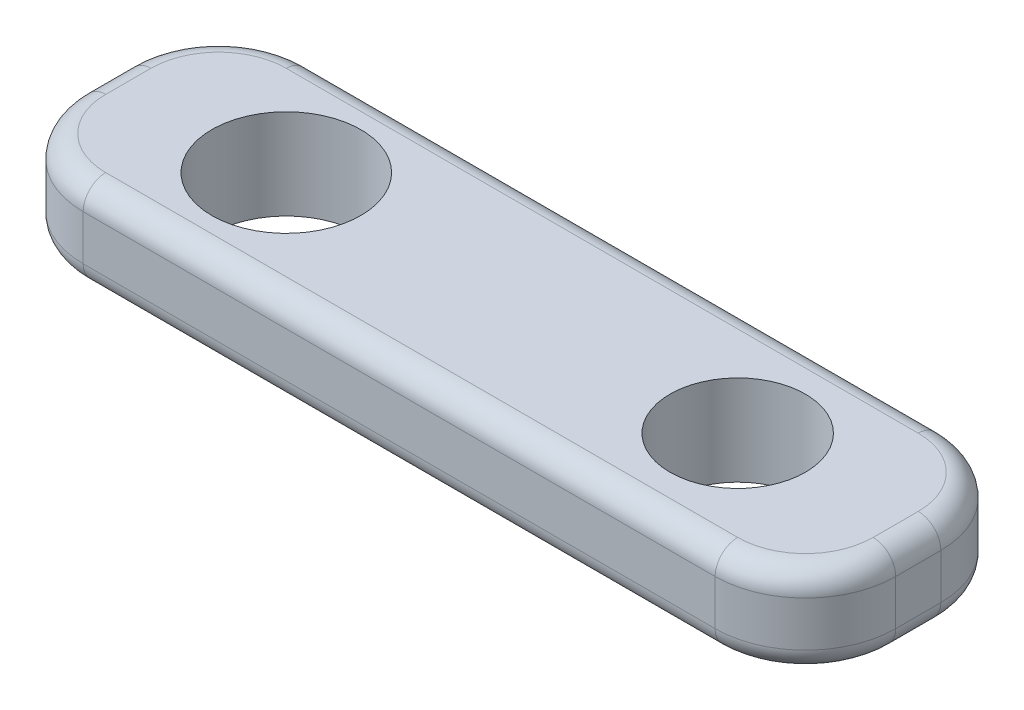
SolidWorks part; units mm, degrees
ref_plane "前视基准面" through (0, 0, 0) normal (0, 0, 1) x (1, 0, 0)
ref_plane "上视基准面" through (0, 0, 0) normal (0, 1, 0) x (1, 0, 0)
ref_plane "右视基准面" through (0, 0, 0) normal (1, 0, 0) x (0, 0, -1)
sketch "草图1" plane through (0, 0, 0) normal (0, 1, 0) x (1, 0, 0)
  line L13 (-7, 2.5) -> (7, 2.5)
  line L14 (-9, 0.5) -> (-9, -0.5)
  line L15 (-7, -2.5) -> (7, -2.5)
  line L16 (9, 0.5) -> (9, -0.5)
  line L17 (-9, 2.5) -> (9, -2.5) construction
  line L18 (-9, -2.5) -> (9, 2.5) construction
  arc A6 (7, 2.5) -> (9, 0.5) centre (7, 0.5) cw
  arc A7 (7, -2.5) -> (9, -0.5) centre (7, -0.5) ccw
  arc A8 (-9, -0.5) -> (-7, -2.5) centre (-7, -0.5) ccw
  arc A9 (-7, 2.5) -> (-9, 0.5) centre (-7, 0.5) ccw
  point P0 (0, 0)
  dimension "D3" = 2
  dimension "D1" = 18
  dimension "D2" = 5
extrude "凸台-拉伸1" add sketch "草图1" along normal blind 2
sketch "草图3" plane through (0, 2, 0) normal (0, 1, 0) x (1, 0, 0)
  line L0 (9, -0.5) -> (9, 0.5) construction
  line L1 (-9, 0.5) -> (-9, -0.5) construction
  circle A0 centre (-5, 0) radius 1.65
  circle A1 centre (5, 0) radius 1.5
  point P6 (-2.8691, 0)
  point P7 (3.2392, 0)
  dimension "D1" = 3.3
  dimension "D2" = 3
  dimension "D3" = 4
  dimension "D4" = 4
extrude "切除-拉伸2" cut sketch "草图3" against normal through all
fillet "圆角1" radius 0.5 16 edges at (8.4142, 2, -1.9142) (9, 2, 0) (8.4142, 2, 1.9142) (0, 2, 2.5) (-8.4142, 2, 1.9142) (-9, 2, 0) (-8.4142, 2, -1.9142) (8.4142, 0, -1.9142) (9, 0, 0) (8.4142, 0, 1.9142) (0, 0, 2.5) (-8.4142, 0, 1.9142) (-9, 0, 0) (-8.4142, 0, -1.9142) (0, 2, -2.5) (0, 0, -2.5)
